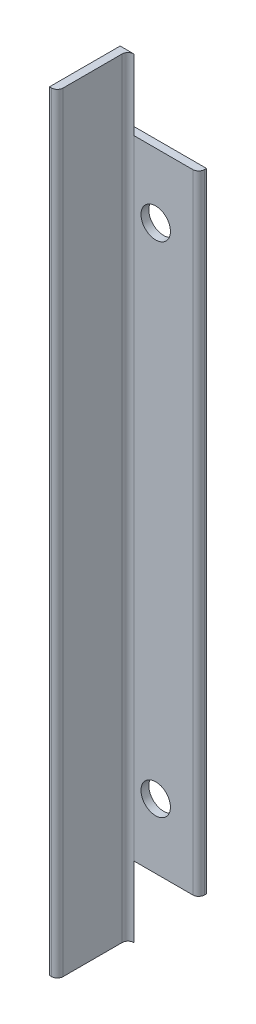
SolidWorks part; units mm, degrees
material "ASTM A36 Steel"
ref_plane "Front Plane" through (0, 0, 0) normal (0, 0, 1) x (1, 0, 0)
ref_plane "Top Plane" through (0, 0, 0) normal (0, 1, 0) x (1, 0, 0)
ref_plane "Right Plane" through (0, 0, 0) normal (1, 0, 0) x (0, 0, -1)
sketch "Sketch1" plane through (0, 0, 0) normal (0, 1, 0) x (1, 0, 0)
  line L0 (-27.4999, 29.2132) -> (-67.4999, 29.2132)
  line L1 (-67.4999, 29.2132) -> (-67.4999, -10.7868)
  line L2 (-67.4999, -10.7868) -> (-66.4999, -10.7868)
  line L3 (-63.4999, -7.7868) -> (-63.4999, 22.2132)
  line L4 (-60.4999, 25.2132) -> (-30.4999, 25.2132)
  line L5 (-27.4999, 28.2132) -> (-27.4999, 29.2132)
  arc A0 (-66.4999, -10.7868) -> (-63.4999, -7.7868) centre (-66.4999, -7.7868) ccw
  arc A1 (-63.4999, 22.2132) -> (-60.4999, 25.2132) centre (-60.4999, 22.2132) cw
  arc A2 (-30.4999, 25.2132) -> (-27.4999, 28.2132) centre (-30.4999, 28.2132) ccw
  point P8 (-63.4999, -10.7868)
  point P13 (-27.4999, 25.2132)
  dimension "D5" = 3
  dimension "D1" = 40
  dimension "D2" = 40
  dimension "D3" = 4
  dimension "D4" = 4
extrude "Boss-Extrude1" add sketch "Sketch1" along normal blind 392
sketch "Sketch2" plane through (-67.4999, 0, 0) normal (-1, 0, 0) x (0, 0, 1)
  line L1 (-29.2132, 392) -> (-25.2132, 392)
  line L2 (-29.2132, 392) -> (-29.2132, 356)
  line L3 (-29.2132, 356) -> (-25.2132, 356)
  line L4 (-25.2132, 392) -> (-25.2132, 356)
  line L5 (-29.2132, 392) -> (-25.2132, 356) construction
  line L6 (-29.2132, 356) -> (-25.2132, 392) construction
  line L8 (-29.2132, 36) -> (-25.2132, 0) construction
  line L9 (-29.2132, 0) -> (-25.2132, 36) construction
  line L10 (-25.2132, 0) -> (-25.2132, 36)
  line L11 (-29.2132, 36) -> (-25.2132, 36)
  line L12 (-29.2132, 0) -> (-29.2132, 36)
  line L13 (-29.2132, 0) -> (-25.2132, 0)
  point P4 (-27.2132, 374)
  point P14 (-27.2132, 18)
  dimension "D1" = 36
  dimension "D2" = 4
extrude "Cut-Extrude1" cut sketch "Sketch2" against normal through all both and the other way through all
sketch "Sketch3" plane through (0, 0, -29.2132) normal (0, 0, -1) x (-1, 0, 0)
  line L1 (27.4999, 356) -> (27.4999, 36) construction
  circle A1 centre (49.3906, 323) radius 7.5
  circle A2 centre (49.3906, 69) radius 7.5
  point P8 (27.4999, 196)
  dimension "D1" = 15
  dimension "D2" = 15
  dimension "D3" = 254
  dimension "D4" = 127
extrude "Cut-Extrude2" cut sketch "Sketch3" against normal through all both and the other way through all
